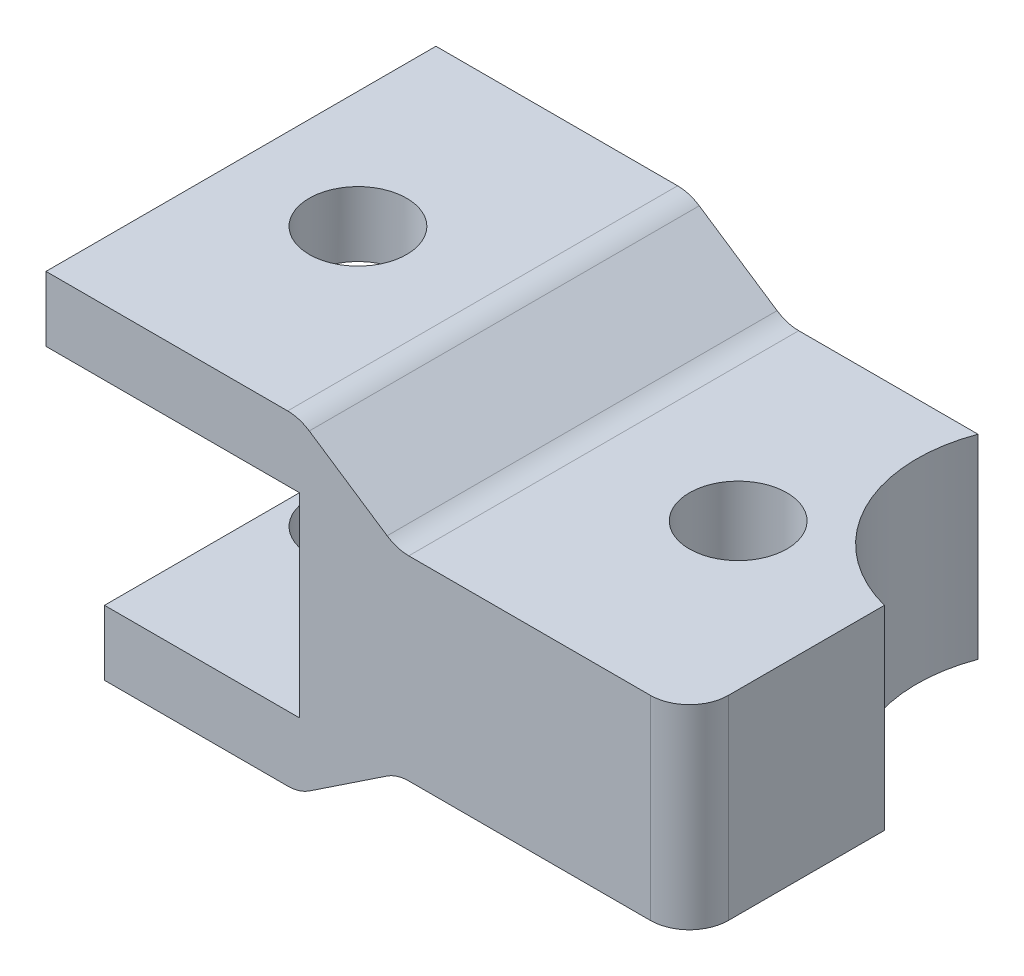
SolidWorks part; units mm, degrees
ref_plane "Front Plane" through (0, 0, 0) normal (0, 0, 1) x (1, 0, 0)
ref_plane "Top Plane" through (0, 0, 0) normal (0, 1, 0) x (1, 0, 0)
ref_plane "Right Plane" through (0, 0, 0) normal (1, 0, 0) x (0, 0, -1)
sketch "Sketch1" plane through (0, 0, 0) normal (0, 0, 1) x (1, 0, 0)
  line L0 (38.1, 0) -> (38.1, 12.7)
  line L1 (0, 0) -> (12.7, 0)
  line L2 (0, 0) -> (0, -4.2316)
  line L3 (0, -4.2316) -> (12.7, -4.2316)
  line L4 (12.7, 0) -> (12.7, -4.2316)
  line L5 (6.35, -4.2316) -> (6.35, 0) construction
  line L6 (0, -2.1158) -> (12.7, -2.1158) construction
  line L8 (12.7, -4.2316) -> (12.7, 16.9316)
  line L12 (12.7, 6.35) -> (38.1, 6.35) construction
  line L13 (12.7, 16.9316) -> (-3.81, 16.9316)
  line L14 (12.7, 16.9316) -> (12.7, 12.7)
  line L15 (12.7, 12.7) -> (-3.81, 12.7)
  line L16 (-3.81, 16.9316) -> (-3.81, 12.7)
  line L17 (4.445, 12.7) -> (4.445, 16.9316) construction
  line L18 (12.7, 14.8158) -> (-3.81, 14.8158) construction
  line L20 (12.7, -4.2316) -> (19.05, 0)
  line L21 (12.7, 16.9316) -> (19.05, 12.7)
  line L22 (19.05, 0) -> (38.1, 0)
  line L23 (19.05, 12.7) -> (38.1, 12.7)
  point P220 (6.35, -2.1158)
  point P325 (25.4, 6.35)
  point P337 (4.445, 14.8158)
  dimension "D1" = 4.2316
  dimension "D2" = 12.7
  dimension "D3" = 12.7
  dimension "D4" = 25.4
  dimension "D5" = 16.51
  dimension "D6" = 6.35
  dimension "D7" = 6.35
  dimension "D8" = 12.7
extrude "Boss-Extrude1" add sketch "Sketch1" along normal blind 25.4
sketch "Sketch4" plane through (0, 0, 0) normal (0, 1, 0) x (1, 0, 0)
  circle A0 centre (3.81, -12.7) radius 3.175
extrude "Cut-Extrude4" cut sketch "Sketch4" against normal through all both and the other way through all
sketch "Sketch6" plane through (0, 12.7, 0) normal (0, 1, 0) x (1, 0, 0)
  line L0 (38.1, -12.7) -> (19.05, -12.7) construction
  line L1 (38.1, -25.4) -> (38.1, 0) construction
  line L2 (19.05, -25.4) -> (19.05, 0) construction
  circle A0 centre (28.575, -12.7) radius 3.175
  dimension "D1" = 6.35
extrude "Cut-Extrude5" cut sketch "Sketch6" against normal through all both and the other way through all
sketch "Sketch7" plane through (0, 12.7, 0) normal (0, 1, 0) x (1, 0, 0)
  line L0 (38.1, -25.4) -> (38.1, 0) construction
  line L1 (19.05, 0) -> (38.1, 0) construction
  line L2 (31.497, 0) -> (38.1, 0)
  line L3 (38.1, 0) -> (38.1, -12.7)
  line L4 (19.05, -25.4) -> (19.05, 0) construction
  arc A1 (31.497, 0) -> (38.1, -12.7) centre (40.5243, -3.373) ccw
  point P14 (31.974, -7.8185)
  dimension "D2" = 12.447
extrude "Cut-Extrude6" cut sketch "Sketch7" against normal through all both and the other way through all
fillet "Fillet1" radius 2.54 5 edges at (12.7, 16.9316, 12.7) (19.05, 12.7, 12.7) (38.1, 6.35, 25.4) (19.05, 0, 12.7) (12.7, -4.2316, 12.7)
